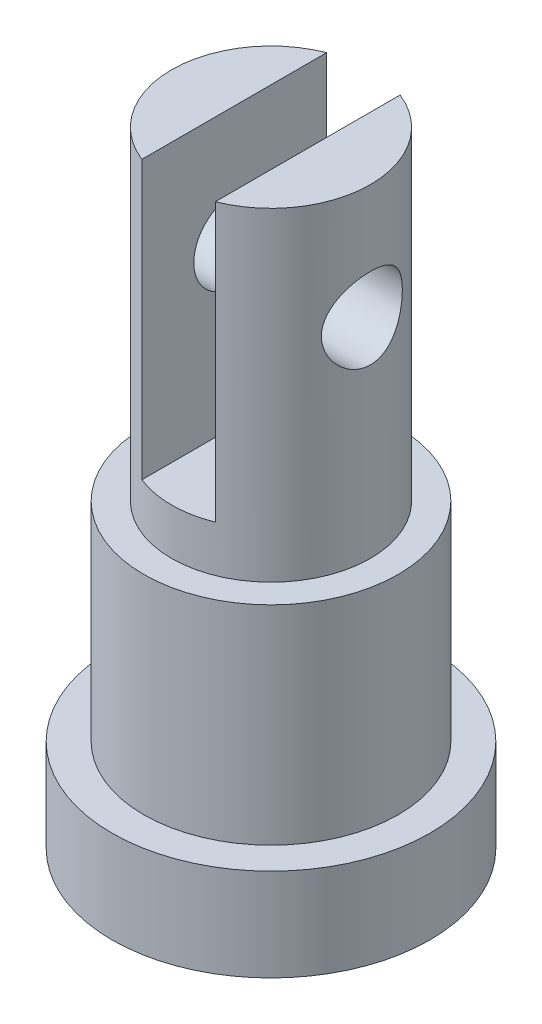
SolidWorks part; units mm, degrees
material "ABS"
ref_plane "Front Plane" through (0, 0, 0) normal (0, 0, 1) x (1, 0, 0)
ref_plane "Top Plane" through (0, 0, 0) normal (0, 1, 0) x (1, 0, 0)
ref_plane "Right Plane" through (0, 0, 0) normal (1, 0, 0) x (0, 0, -1)
sketch "Sketch1" plane through (0, 0, 0) normal (0, 1, 0) x (1, 0, 0)
  circle A0 centre (0, 0) radius 6.875
  dimension "D1" = 13.75
extrude "Boss-Extrude1" add sketch "Sketch1" along normal blind 4
sketch "Sketch2" plane through (0, 4, 0) normal (0, 1, 0) x (1, 0, 0)
  circle A2 centre (0, 0) radius 5.5
  point P0 (0, 0)
  dimension "D1" = 11
extrude "Boss-Extrude2" add sketch "Sketch2" along normal blind 9
sketch "Sketch3" plane through (0, 13, 0) normal (0, 1, 0) x (1, 0, 0)
  circle A0 centre (0, 0) radius 4.3
  dimension "D1" = 8.6
extrude "Boss-Extrude3" add sketch "Sketch3" along normal blind 14
sketch "Sketch4" plane through (0, 27, 0) normal (0, 1, 0) x (1, 0, 0)
  line L1 (-1.5875, 4.3) -> (1.5875, 4.3)
  line L2 (-1.5875, 4.3) -> (-1.5875, -4.3)
  line L3 (-1.5875, -4.3) -> (1.5875, -4.3)
  line L4 (1.5875, 4.3) -> (1.5875, -4.3)
  line L5 (-1.5875, 4.3) -> (1.5875, -4.3) construction
  line L6 (-1.5875, -4.3) -> (1.5875, 4.3) construction
  point P0 (0, 0)
  dimension "D1" = 8.6
  dimension "D2" = 3.175
extrude "Cut-Extrude1" cut sketch "Sketch4" against normal blind 12
sketch "Sketch5" plane through (1.5875, 0, 0) normal (-1, 0, 0) x (0, 0, 1)
  line L0 (3.9962, 15) -> (-3.9962, 15) construction
  line L1 (3.9962, 27) -> (-3.9962, 27) construction
  line L2 (3.9962, 15) -> (-3.9962, 15)
  line L3 (3.9962, 27) -> (-3.9962, 27)
  line L4 (0, 15) -> (0, 22) construction
  circle A0 centre (0, 22) radius 1.75
  dimension "D2" = 3.5
  dimension "D1" = 7
extrude "Cut-Extrude2" cut sketch "Sketch5" against normal through all both and the other way through all contours A0
equation "\"prop-dist\"= 70mm"
equation "\"prop-hole-depth\"= 9mm"
equation "\"prop-hole-diameter\"= 11mm"
equation "\"rivet-extension\" = 12mm"
equation "\"rivet-hole-extension\"= 7mm"
equation "\"rivet-hole-diameter\"= 3.5mm"
equation "\"ski-length\"= 100mm"
equation "\"th\"= 0.125in'material thickness"
equation "\"ski-height\"= 30mm"
equation "\"ski-curve-gap\"= 60mm"
equation "\"ski-curve-height\"= \"rivet-hole-extension\""
equation "\"min-width\"= 4mm"
equation "\"prop-hole-diameter-small\"= 8.6mm"
equation "\"D1@Sketch1\"=\"prop-hole-diameter\"*1.25"
equation "\"D1@Sketch2\"=\"prop-hole-diameter\""
equation "\"D1@Boss-Extrude2\"=\"prop-hole-depth\""
equation "\"D1@Sketch3\"=\"prop-hole-diameter-small\""
equation "\"D1@Boss-Extrude3\"=\"rivet-extension\"+2mm"
equation "\"D1@Sketch4\"=\"prop-hole-diameter-small\""
equation "\"D2@Sketch4\"=\"th\""
equation "\"D1@Cut-Extrude1\"=\"rivet-extension\""
equation "\"D1@Sketch5\"=\"rivet-hole-extension\""
equation "\"D2@Sketch5\"=\"rivet-hole-diameter\""
